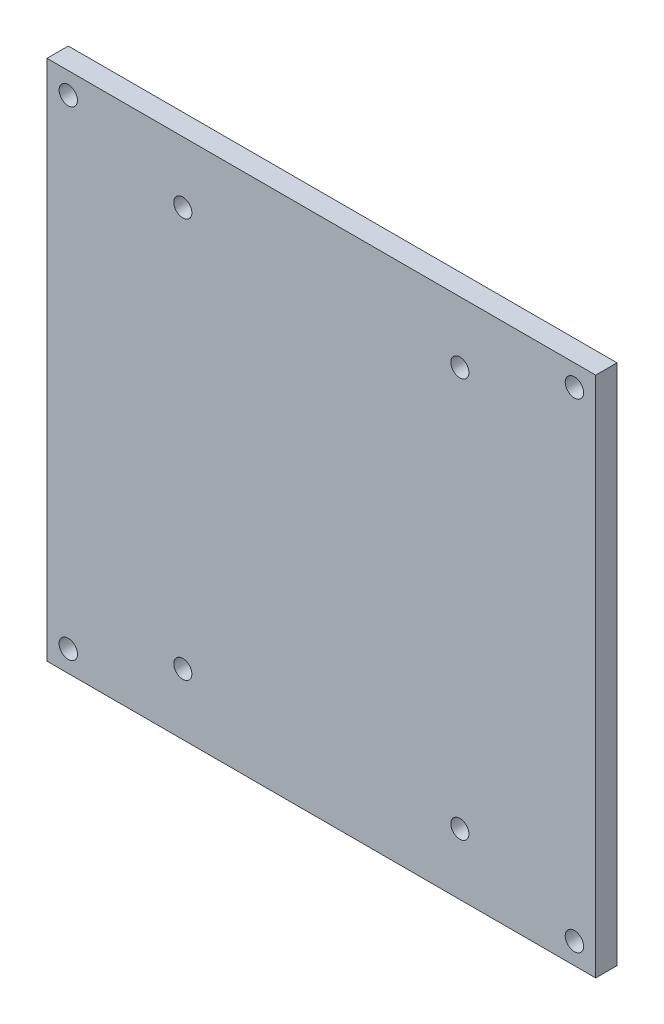
SolidWorks part; units mm, degrees
ref_plane "Спереди" through (0, 0, 0) normal (0, 0, 1) x (1, 0, 0)
ref_plane "Сверху" through (0, 0, 0) normal (0, 1, 0) x (1, 0, 0)
ref_plane "Справа" through (0, 0, 0) normal (1, 0, 0) x (0, 0, -1)
other "Configuration Table"
sketch "Эскиз1" plane through (0, 0, 0) normal (0, 0, 1) x (1, 0, 0)
  line L1 (-51.5, 49) -> (51.5, 49)
  line L2 (-51.5, 49) -> (-51.5, -49)
  line L3 (-51.5, -49) -> (51.5, -49)
  line L4 (51.5, 49) -> (51.5, -49)
  line L5 (-51.5, 49) -> (51.5, -49) construction
  line L6 (-51.5, -49) -> (51.5, 49) construction
  point P0 (0, 0)
  dimension "D1" = 103
  dimension "D2" = 98
extrude "Бобышка-Вытянуть1" add sketch "Эскиз1" along normal blind 4
sketch "Эскиз2" plane through (0, 0, 4) normal (0, 0, 1) x (1, 0, 0)
  circle A0 centre (-47.5, 45) radius 1.725
  circle A1 centre (47.5, 45) radius 1.725
  circle A2 centre (47.5, -45) radius 1.725
  circle A3 centre (-47.5, -45) radius 1.725
  point P0 (0, 0)
  dimension "D3" = 3.45
  dimension "D4" = 3.45
  dimension "D5" = 3.45
  dimension "D6" = 3.45
  dimension "D1" = 90
  dimension "D2" = 95
extrude "Вырез-Вытянуть1" cut sketch "Эскиз2" against normal blind 4
sketch "Эскиз3" plane through (0, 0, 4) normal (0, 0, 1) x (1, 0, 0)
  circle A0 centre (-26, 37.5) radius 1.7
  circle A1 centre (26, 37.5) radius 1.7
  circle A2 centre (-26, -37.5) radius 1.7
  circle A3 centre (26, -37.5) radius 1.7
  point P4 (0, 0)
  dimension "D3" = 3.4
  dimension "D4" = 3.4
  dimension "D5" = 3.4
  dimension "D6" = 3.4
  dimension "D1" = 52
  dimension "D2" = 75
extrude "Вырез-Вытянуть2" cut sketch "Эскиз3" against normal blind 4
equation "\"D4@Эскиз2\"=\"D3@Эскиз2\""
equation "\"D5@Эскиз2\"=\"D3@Эскиз2\""
equation "\"D6@Эскиз2\"=\"D3@Эскиз2\""
